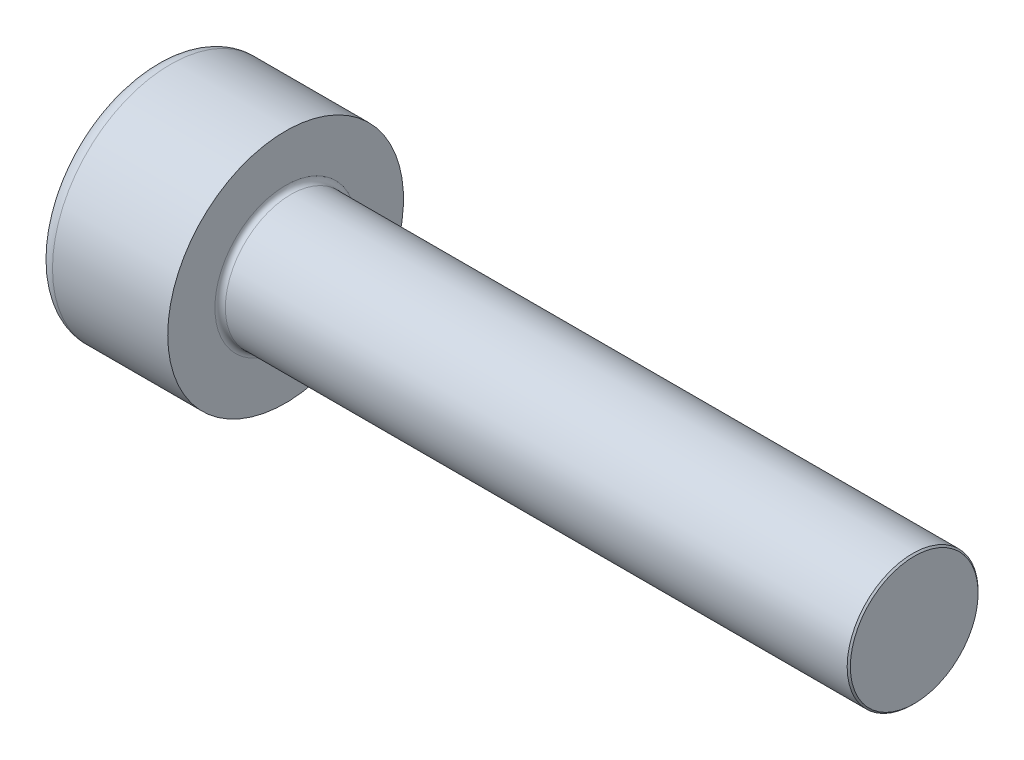
SolidWorks part; units mm, degrees
material "Ст3пс ГОСТ 380-2005"
ref_plane "Plane1" through (0, 0, 0) normal (0, 0, 1) x (1, 0, 0)
ref_plane "Plane2" through (0, 0, 0) normal (0, 1, 0) x (1, 0, 0)
ref_plane "Plane3" through (0, 0, 0) normal (1, 0, 0) x (0, 0, -1)
sketch "BodySke" plane through (0, 0, 0) normal (0, 0, 1) x (1, 0, 0)
  line L0 (0, 0) -> (0, 2.25)
  line L1 (0, 2.25) -> (2.5, 2.25)
  line L2 (2.5, 2.25) -> (2.5, 1.25)
  line L3 (2.5, 1.25) -> (14.4695, 1.25)
  line L4 (14.5, 1.2195) -> (14.5, 0)
  line L5 (14.5, 0) -> (0, 0)
  line L6 (-31.75, 0) -> (127, 0) construction
  line L8 (14.5, 1.2195) -> (14.4695, 1.25)
  line L10 (14.5, -1.2195) -> (14.4695, -1.25) construction
  line L11 (3, 9.525) -> (3, 3.175) construction
  line L12 (2.5, 9.525) -> (2.5, 3.175) construction
  line L13 (-45.5, 9.525) -> (-45.5, 3.175) construction
  dimension "Head_ht" = 2.5
  dimension "Length" = 12
  dimension "Body_ch_ang" = 45
  dimension "Diameter" = 2.5
  dimension "Minor_dia" = 2.439
  dimension "Advance" = 0.5
  dimension "Thread_nom" = 12
  dimension "Thread_length" = 60
  dimension "Head_dia" = 4.5
revolve "Base-Revolve" add sketch "BodySke" angle 360 about L6
cosmetic thread "ThreadCosmetic" [suppressed] parameters "Thread_length"=10.5, "Thread_minor"=2.439
fillet "Fillet1" radius 0.1 1 edges at (2.5, 0, 1.25)
fillet "Fillet2" radius 0.3 1 edges at (0, 0, 2.25)
sketch "Sketch2" plane through (0, 0, 0) normal (0, 0, 1) x (1, 0, 0)
  line L0 (0, 1) -> (1.3, 1)
  line L1 (1.3, 1) -> (1.8774, 0)
  line L2 (-31.75, 0) -> (127, 0) construction
  line L3 (1.8774, 0) -> (0, 0)
  line L4 (0, 0) -> (0, 1)
  line L6 (0, 0) -> (47.625, 0) construction
  dimension "D1" = 1
  dimension "D2" = 60
  dimension "Depth" = 1.3
revolve "Hex-PreBroach" cut sketch "Sketch2" angle 360 about L6
sketch "Sketch3" plane through (0, 0, 0) normal (-1, 0, 0) x (0, 0.5, 0.866)
  line L0 (0.5774, 1) -> (-0.5774, 1)
  line L1 (-0.5774, 1) -> (-1.1547, 0)
  line L2 (0.5774, 1) -> (1.1547, 0)
  line L3 (0.5774, -1) -> (1.1547, 0)
  line L4 (0.5774, -1) -> (-0.5774, -1)
  line L5 (-0.5774, -1) -> (-1.1547, 0)
  dimension "D1" = 1
  dimension "D2" = 1
  dimension "Hex_size" = 2
extrude "Hex" cut sketch "Sketch3" against normal blind 1.3
equation "\"D2@Sketch3\"=\"Hex_size@Sketch3\" / 2"
equation "\"D1@Sketch3\"=\"Hex_size@Sketch3\" / 2"
equation "\"D1@Sketch2\"=\"Hex_size@Sketch3\" / 2"
equation "\"Thread_minor@ThreadCosmetic\"=\"Minor_dia@BodySke\""
equation "\"Depth@Sketch2\"=\"Key_eng@Hex\""
equation "\"Thread_length@ThreadCosmetic\"=((sgn( (\"Length@BodySke\" - \"Advance@BodySke\" * 3.0) - \"Thread_nom@BodySke\" )-1)*( (\"Length@BodySke\" - \"Advance@BodySke\" * 3.0) - \"Thread_nom@BodySke\" ))/-2+ \"Thread_nom@BodySke\""
